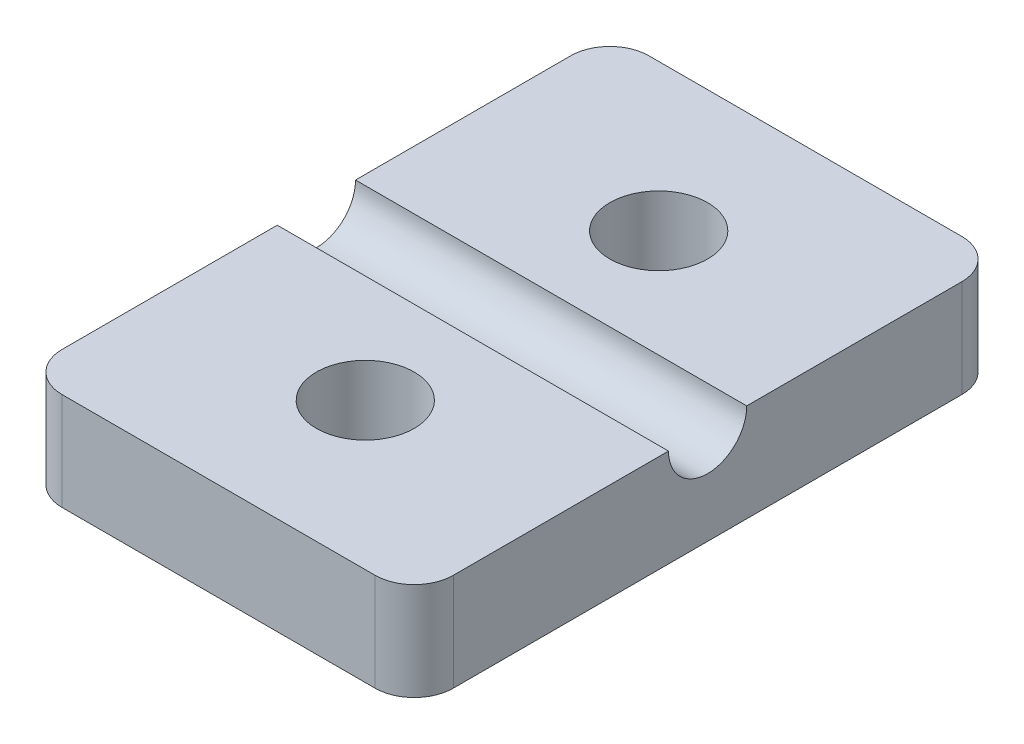
SolidWorks part; units mm, degrees
ref_plane "前视基准面" through (0, 0, 0) normal (0, 0, 1) x (1, 0, 0)
ref_plane "上视基准面" through (0, 0, 0) normal (0, 1, 0) x (1, 0, 0)
ref_plane "右视基准面" through (0, 0, 0) normal (1, 0, 0) x (0, 0, -1)
sketch "草图1" plane through (0, 0, 0) normal (1, 0, 0) x (0, 0, -1)
  line L1 (-7.5, 1.25) -> (7.5, 1.25)
  line L2 (-7.5, 1.25) -> (-7.5, -1.25)
  line L3 (-7.5, -1.25) -> (7.5, -1.25)
  line L4 (7.5, 1.25) -> (7.5, -1.25)
  line L5 (-7.5, 1.25) -> (7.5, -1.25) construction
  line L6 (-7.5, -1.25) -> (7.5, 1.25) construction
  circle A0 centre (0, 1.25) radius 1
  point P0 (0, 0)
  dimension "D3" = 2
  dimension "D1" = 15
  dimension "D2" = 2.5
extrude "凸台-拉伸1" add sketch "草图1" along normal blind 10 contours A0 L1 L2 L3 L4
sketch "草图2" plane through (0, 1.25, 0) normal (0, 1, 0) x (1, 0, 0)
  line L0 (10, 7.5) -> (0, 7.5) construction
  circle A0 centre (5, 3.75) radius 1.25
  circle A1 centre (5, -3.75) radius 1.25
  point P6 (5, 7.5)
  dimension "D1" = 7.5
  dimension "D3" = 2.5
  dimension "D2" = 3.75
extrude "切除-拉伸1" cut sketch "草图2" against normal through all
fillet "圆角1" radius 1 4 edges at (0, 0, 7.5) (10, 0, 7.5) (0, 0, -7.5) (10, 0, -7.5)
